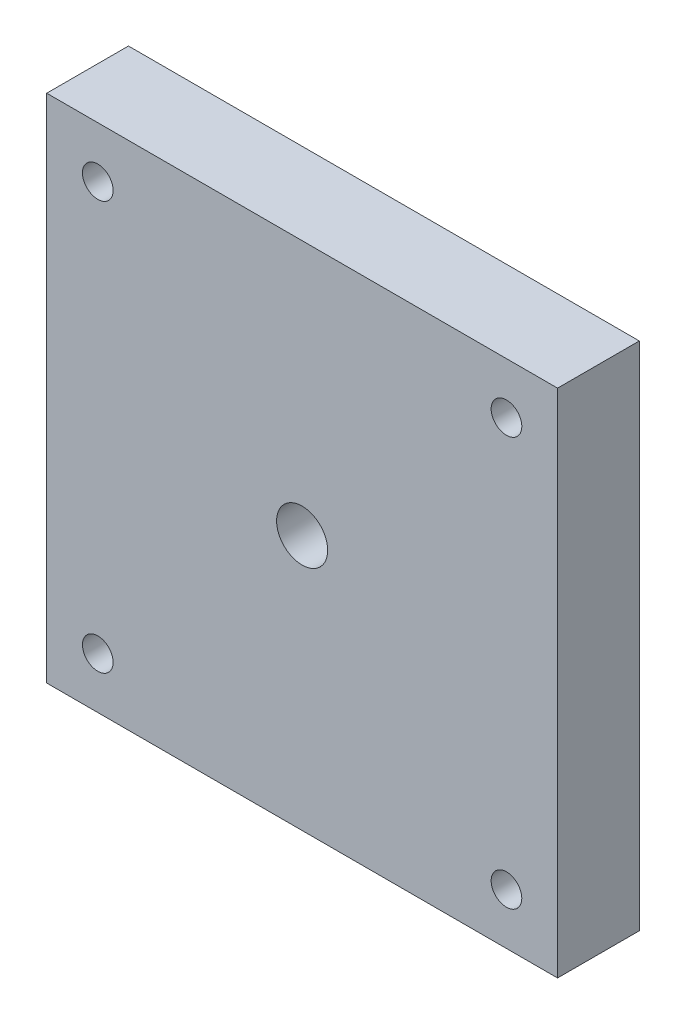
SolidWorks part; units mm, degrees
ref_plane "前视基准面" through (0, 0, 0) normal (0, 0, 1) x (1, 0, 0)
ref_plane "上视基准面" through (0, 0, 0) normal (0, 1, 0) x (1, 0, 0)
ref_plane "右视基准面" through (0, 0, 0) normal (1, 0, 0) x (0, 0, -1)
sketch "草图1" plane through (0, 0, 0) normal (0, 0, 1) x (1, 0, 0)
  line L0 (0, 24.2958) -> (0, -18.2642) construction
  line L1 (-25, 25) -> (25, 25)
  line L2 (-25, 25) -> (-25, -25)
  line L3 (-25, -25) -> (25, -25)
  line L4 (25, 25) -> (25, -25)
  line L5 (-32.2198, 0) -> (32.714, 0) construction
  circle A0 centre (0, 0) radius 2.5
  circle A1 centre (-20, 20) radius 1.5
  circle A2 centre (20, 20) radius 1.5
  circle A3 centre (20, -20) radius 1.5
  circle A4 centre (-20, -20) radius 1.5
  dimension "D1" = 5
  dimension "D6" = 3
  dimension "D8" = 20
  dimension "D2" = 50
  dimension "D3" = 50
  dimension "D4" = 25
  dimension "D5" = 25
  dimension "D7" = 20
extrude "凸台-拉伸1" add sketch "草图1" along normal blind 8
